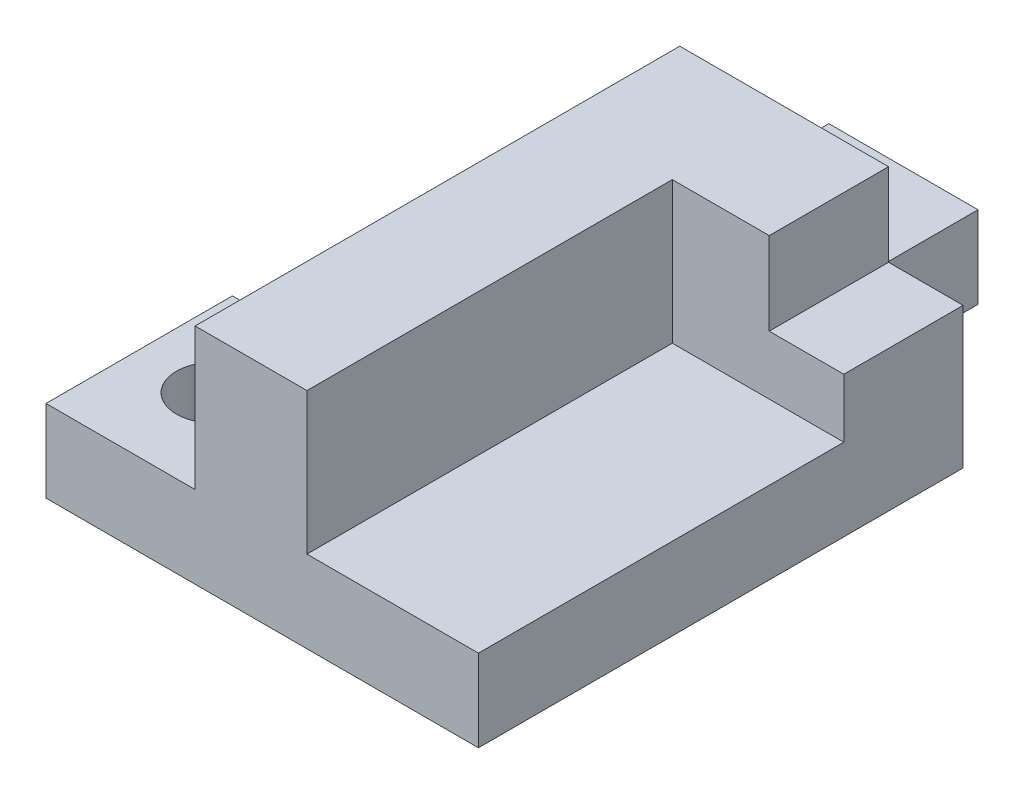
SolidWorks part; units mm, degrees
ref_plane "Front Plane" through (0, 0, 0) normal (0, 0, 1) x (1, 0, 0)
ref_plane "Top Plane" through (0, 0, 0) normal (0, 1, 0) x (1, 0, 0)
ref_plane "Right Plane" through (0, 0, 0) normal (1, 0, 0) x (0, 0, -1)
sketch "Sketch1" plane through (0, 0, 0) normal (0, 1, 0) x (1, 0, 0)
  line L1 (-184.5, -100) -> (184.5, -100)
  line L2 (-184.5, -100) -> (-184.5, 100)
  line L3 (-184.5, 100) -> (184.5, 100)
  line L4 (184.5, -100) -> (184.5, 100)
  line L5 (-184.5, -100) -> (184.5, 100) construction
  line L6 (-184.5, 100) -> (184.5, -100) construction
  point P0 (0, 0)
  dimension "D1" = 200
  dimension "353" = 369
extrude "Boss-Extrude1" add sketch "Sketch1" along normal blind 20
sketch "Sketch2" plane through (0, 20, 0) normal (0, 1, 0) x (1, 0, 0)
  line L0 (-184.5, -100) -> (184.5, -100) construction
  line L1 (-184.5, -100) -> (-169.5, -100)
  line L2 (-184.5, -100) -> (-184.5, -35)
  line L3 (-184.5, -35) -> (-169.5, -35)
  line L4 (-169.5, -84) -> (-169.5, -35)
  line L5 (-184.5, 100) -> (-169.5, 100)
  line L6 (-184.5, 100) -> (-184.5, 35)
  line L7 (-184.5, 35) -> (-169.5, 35)
  line L8 (-169.5, 84) -> (-169.5, 35)
  line L9 (-169.5, 100) -> (-119.5, 100)
  line L11 (-169.5, 84) -> (-119.5, 84)
  line L12 (-119.5, 100) -> (-119.5, 84)
  line L13 (-169.5, -100) -> (-119.5, -100)
  line L15 (-169.5, -84) -> (-119.5, -84)
  line L16 (-119.5, -100) -> (-119.5, -84)
  line L17 (-44.5, -100) -> (84.5, -100)
  line L18 (-44.5, -100) -> (-44.5, -84)
  line L19 (-44.5, -84) -> (84.5, -84)
  line L20 (84.5, -100) -> (84.5, -84)
  line L21 (184.5, 100) -> (-184.5, 100) construction
  line L22 (-44.5, 100) -> (84.5, 100)
  line L23 (-44.5, 100) -> (-44.5, 84)
  line L24 (-44.5, 84) -> (84.5, 84)
  line L25 (84.5, 100) -> (84.5, 84)
  line L26 (184.5, -100) -> (184.5, 100) construction
  point P28 (84.5, -92)
  dimension "D1" = 65
  dimension "D2" = 15
  dimension "D3" = 65
  dimension "D4" = 15
  dimension "D5" = 16
  dimension "D6" = 50
  dimension "D7" = 50
  dimension "D8" = 16
  dimension "D9" = 75
  dimension "D10" = 100
extrude "Boss-Extrude2" add sketch "Sketch2" along normal blind 10
sketch "Sketch3" plane through (0, 20, 0) normal (0, 1, 0) x (1, 0, 0)
  line L0 (-119.5, -84) -> (-169.5, -84) construction
  line L1 (-169.5, 84) -> (172.5, 84)
  line L2 (-169.5, 84) -> (-169.5, -84)
  line L3 (-169.5, -84) -> (172.5, -84)
  line L4 (172.5, 84) -> (172.5, -84)
  dimension "D1" = 342
extrude "Cut-Extrude1" cut sketch "Sketch3" against normal blind 9
sketch "Sketch4" plane through (0, 0, -100) normal (0, 0, -1) x (-1, 0, 0)
  line L0 (-84.5, 30) -> (44.5, 30) construction
  line L1 (-69.5, 20) -> (30.5, 20)
  line L2 (-69.5, 20) -> (-69.5, 30)
  line L3 (-69.5, 30) -> (30.5, 30)
  line L4 (30.5, 20) -> (30.5, 30)
  line L5 (-69.5, 20) -> (30.5, 30) construction
  line L6 (-69.5, 30) -> (30.5, 20) construction
  line L8 (-84.5, 30) -> (-84.5, 20) construction
  point P0 (-19.5, 25)
  dimension "D1" = 100
  dimension "D2" = 15
extrude "Boss-Extrude3" add sketch "Sketch4" along normal blind 60
sketch "Sketch6" plane through (0, 0, -84) normal (0, 0, 1) x (1, 0, 0)
  line L0 (-24.5, 30) -> (-26.0308, 28.0811)
  line L1 (-44.5, 30) -> (84.5, 30) construction
  line L2 (-25.1938, 26.3428) -> (-15.8062, 26.3428)
  line L3 (-14.9692, 28.0811) -> (-16.5, 30)
  line L4 (-16.5, 30) -> (-24.5, 30)
  line L5 (-44.5, 30) -> (84.5, 30) construction
  line L6 (-44.5, 30) -> (-44.5, 20) construction
  line L7 (56.5, 30) -> (54.982, 27.8015)
  line L8 (55.8062, 26.2309) -> (65.1938, 26.2309)
  line L9 (66.018, 27.8015) -> (64.5, 30)
  line L10 (64.5, 30) -> (56.5, 30)
  line L12 (84.5, 30) -> (84.5, 20) construction
  arc A0 (-26.0308, 28.0811) -> (-25.1938, 26.3428) centre (-25.1938, 27.4134) ccw
  arc A1 (-15.8062, 26.3428) -> (-14.9692, 28.0811) centre (-15.8062, 27.4134) ccw
  arc A2 (54.982, 27.8015) -> (55.8062, 26.2309) centre (55.8062, 27.2324) ccw
  arc A3 (65.1938, 26.2309) -> (66.018, 27.8015) centre (65.1938, 27.2324) ccw
  dimension "D1" = 8
  dimension "D2" = 20
  dimension "D3" = 8
  dimension "D4" = 20
extrude "Cut-Extrude3" cut sketch "Sketch6" against normal blind 60 and the other way blind 10
sketch "Sketch10" plane through (0, 30, 0) normal (0, 1, 0) x (1, 0, 0)
  line L1 (-146.5, 161.5046) -> (257.5, 161.5046)
  line L2 (-146.5, 161.5046) -> (-146.5, -163.2916)
  line L3 (-146.5, -163.2916) -> (257.5, -163.2916)
  line L4 (257.5, 161.5046) -> (257.5, -163.2916)
  line L6 (-184.5, 35) -> (-184.5, -35) construction
  dimension "D1" = 38
  dimension "D2" = 404
extrude "Cut-Extrude4" cut sketch "Sketch10" against normal blind 69
sketch "Sketch14" plane through (0, 0, -100) normal (0, 0, -1) x (-1, 0, 0)
  line L6 (119.5, 53.6124) -> (156.5, 53.6124)
  line L7 (119.5, 53.6124) -> (119.5, 18.895)
  line L8 (119.5, 18.895) -> (156.5, 18.895)
  line L9 (156.5, 53.6124) -> (156.5, 18.895)
  line L10 (184.5, 30) -> (184.5, 0) construction
  dimension "D1" = 28
extrude "Cut-Extrude7" cut sketch "Sketch14" against normal through all both and the other way through all
sketch "Sketch12" plane through (-184.5, 0, 0) normal (-1, 0, 0) x (0, 0, 1)
  line L1 (0, 0) -> (-50, 0)
  line L2 (0, 0) -> (0, 11)
  line L3 (0, 11) -> (-50, 11)
  line L4 (-50, 0) -> (-50, 11)
  dimension "D1" = 11
  dimension "D2" = 50
extrude "Boss-Extrude6" add sketch "Sketch12" along normal blind 20
sketch "Sketch13" plane through (0, 11, 0) normal (0, 1, 0) x (1, 0, 0)
  line L0 (-204.5, 0) -> (-204.5, 50) construction
  line L1 (-204.5, 50) -> (-184.5, 50) construction
  circle A0 centre (-194.5, 25) radius 4
  dimension "D1" = 10
  dimension "D2" = 25
extrude "Cut-Extrude6" cut sketch "Sketch13" against normal through all
sketch "Croquis3" plane through (0, 30, 0) normal (0, 1, 0) x (1, 0, 0)
  line L0 (16.1657, 0) -> (-146.5, 0)
  line L1 (-16.5, 0) -> (16.5, 0) construction
  line L2 (-146.5, -35) -> (-204.5, -35)
  line L3 (-146.5, 84) -> (-146.5, -84) construction
  line L4 (-204.5, 0) -> (-204.5, 50) construction
  line L5 (-204.5, -35) -> (-204.5, 35)
  line L7 (-146.5, 35) -> (-146.5, -35)
  line L8 (-146.5, 35) -> (-204.5, 35)
  line L9 (-204.5, 0) -> (-245.6879, 0)
  line M10 (-169.5, -35) -> (-184.5, -35)
extrude "Cortar-Extruir4" cut sketch "Croquis3" against normal blind 220 contours L7 L8 L5 L2 M10
sketch "Croquis5" plane through (0, 0, -50) normal (0, 0, -1) x (-1, 0, 0)
  line L0 (184.5, 11) -> (204.5, 11)
  line L1 (204.5, 11) -> (204.5, 0)
  line L2 (204.5, 0) -> (184.5, 0)
  line L3 (184.5, 0) -> (184.5, 11)
extrude "Saliente-Extruir2" add sketch "Croquis5" along normal blind 10
sketch "Croquis6" plane through (0, 0, -100) normal (0, 0, -1) x (-1, 0, 0)
  line L0 (184.5, 11) -> (164.5, 11)
  line L1 (164.5, 11) -> (164.5, 0)
  line L2 (146.5, 0) -> (184.5, 0) construction
  line L3 (164.5, 0) -> (184.5, 0)
  line L4 (184.5, 0) -> (184.5, 11)
  dimension "D1" = 20
extrude "Saliente-Extruir3" add sketch "Croquis6" along normal blind 20
sketch "Croquis8" plane through (0, 11, 0) normal (0, 1, 0) x (1, 0, 0)
  circle A0 centre (-194.5, 47.5) radius 5
  circle A1 centre (-194.5, -47.5) radius 5
  circle A2 centre (-174.5, -110) radius 5
  circle A3 centre (-174.5, 110) radius 5
  dimension "D1" = 10
  dimension "D2" = 10
  dimension "D3" = 10
  dimension "D4" = 10
extrude "Cortar-Extruir5" cut sketch "Croquis8" against normal blind 48
sketch "Croquis9" plane through (0, 30, 0) normal (0, 1, 0) x (1, 0, 0)
  line L0 (-184.5, -35) -> (-146.5, -35)
  line L1 (-146.5, -35) -> (-146.5, -100)
  line L2 (-146.5, -100) -> (-184.5, -100)
  line L3 (-184.5, -100) -> (-184.5, -35)
extrude "Cortar-Extruir6" cut sketch "Croquis9" against normal blind 85
